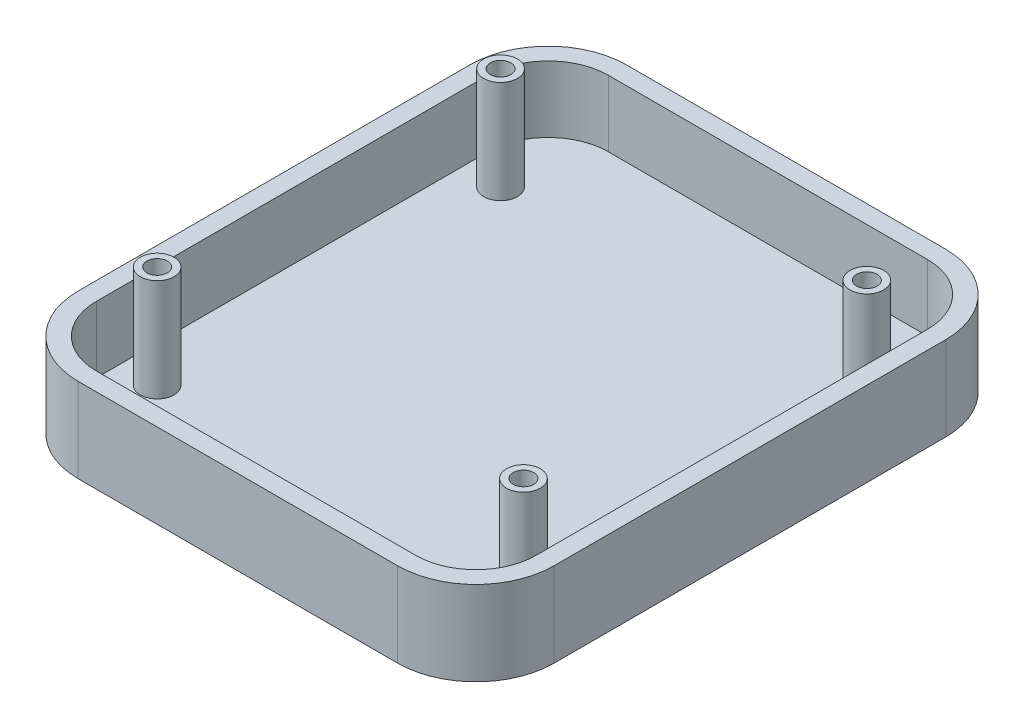
SolidWorks part; units mm, degrees
ref_plane "前视基准面" through (0, 0, 0) normal (0, 0, 1) x (1, 0, 0)
ref_plane "上视基准面" through (0, 0, 0) normal (0, 1, 0) x (1, 0, 0)
ref_plane "右视基准面" through (0, 0, 0) normal (1, 0, 0) x (0, 0, -1)
sketch "草图1" plane through (0, 0, 0) normal (0, 1, 0) x (1, 0, 0)
  line L1 (-18.25, 21.25) -> (18.25, 21.25)
  line L2 (-18.25, 21.25) -> (-18.25, -21.25)
  line L3 (-18.25, -21.25) -> (18.25, -21.25)
  line L4 (18.25, 21.25) -> (18.25, -21.25)
  line L5 (-18.25, 21.25) -> (18.25, -21.25) construction
  line L6 (-18.25, -21.25) -> (18.25, 21.25) construction
  point P0 (0, 0)
  dimension "D1" = 36.5
  dimension "D2" = 42.5
extrude "凸台-拉伸1" add sketch "草图1" along normal blind 1.5
fillet "圆角1" radius 5 4 edges at (18.25, 0.75, 21.25) (-18.25, 0.75, 21.25) (-18.25, 0.75, -21.25) (18.25, 0.75, -21.25)
sketch "草图2" plane through (0, 1.5, 0) normal (0, 1, 0) x (1, 0, 0)
  line L0 (0, 0) -> (-18.25, 0) construction
  line L1 (-18.25, 16.25) -> (-18.25, -16.25) construction
  line L2 (0, 0) -> (0, 21.25) construction
  line L3 (13.25, 21.25) -> (-13.25, 21.25) construction
  circle A0 centre (-15.2, 14.25) radius 1.4
  circle A1 centre (-15.2, 14.25) radius 0.85
  circle A2 centre (-15.2, -14.25) radius 0.85
  circle A3 centre (-15.2, -14.25) radius 1.4
  circle A4 centre (15.2, -14.25) radius 1.4
  circle A5 centre (15.2, -14.25) radius 0.85
  circle A6 centre (15.2, 14.25) radius 0.85
  circle A7 centre (15.2, 14.25) radius 1.4
  dimension "D1" = 2.8
  dimension "D2" = 1.7
  dimension "D3" = 30.4
  dimension "D4" = 28.5
extrude "凸台-拉伸2" add sketch "草图2" along normal blind 8.5
sketch "草图3" plane through (0, 1.5, 0) normal (0, 1, 0) x (1, 0, 0)
  line L0 (-13.25, -22.75) -> (13.25, -22.75)
  line L1 (19.75, -16.25) -> (19.75, 16.25)
  line L2 (13.25, 22.75) -> (-13.25, 22.75)
  line L3 (-19.75, 16.25) -> (-19.75, -16.25)
  line L4 (-13.25, -21.25) -> (13.25, -21.25)
  line L5 (18.25, -16.25) -> (18.25, 16.25)
  line L6 (13.25, 21.25) -> (-13.25, 21.25)
  line L7 (-18.25, 16.25) -> (-18.25, -16.25)
  line L8 (-13.25, -21.25) -> (13.25, -21.25)
  line L9 (18.25, -16.25) -> (18.25, 16.25)
  line L10 (13.25, 21.25) -> (-13.25, 21.25)
  line L11 (-18.25, 16.25) -> (-18.25, -16.25)
  arc A0 (13.25, -22.75) -> (19.75, -16.25) centre (13.25, -16.25) ccw
  arc A1 (19.75, 16.25) -> (13.25, 22.75) centre (13.25, 16.25) ccw
  arc A2 (-13.25, 22.75) -> (-19.75, 16.25) centre (-13.25, 16.25) ccw
  arc A3 (-19.75, -16.25) -> (-13.25, -22.75) centre (-13.25, -16.25) ccw
  arc A4 (13.25, -21.25) -> (18.25, -16.25) centre (13.25, -16.25) ccw
  arc A5 (18.25, 16.25) -> (13.25, 21.25) centre (13.25, 16.25) ccw
  arc A6 (-13.25, 21.25) -> (-18.25, 16.25) centre (-13.25, 16.25) ccw
  arc A7 (-18.25, -16.25) -> (-13.25, -21.25) centre (-13.25, -16.25) ccw
  arc A8 (13.25, -21.25) -> (18.25, -16.25) centre (13.25, -16.25) ccw
  arc A9 (18.25, 16.25) -> (13.25, 21.25) centre (13.25, 16.25) ccw
  arc A10 (-13.25, 21.25) -> (-18.25, 16.25) centre (-13.25, 16.25) ccw
  arc A11 (-18.25, -16.25) -> (-13.25, -21.25) centre (-13.25, -16.25) ccw
  dimension "D1" = 0
  dimension "D2" = 1.5
extrude "凸台-拉伸3" add sketch "草图3" along normal blind 5.5 and the other way blind 1.5
